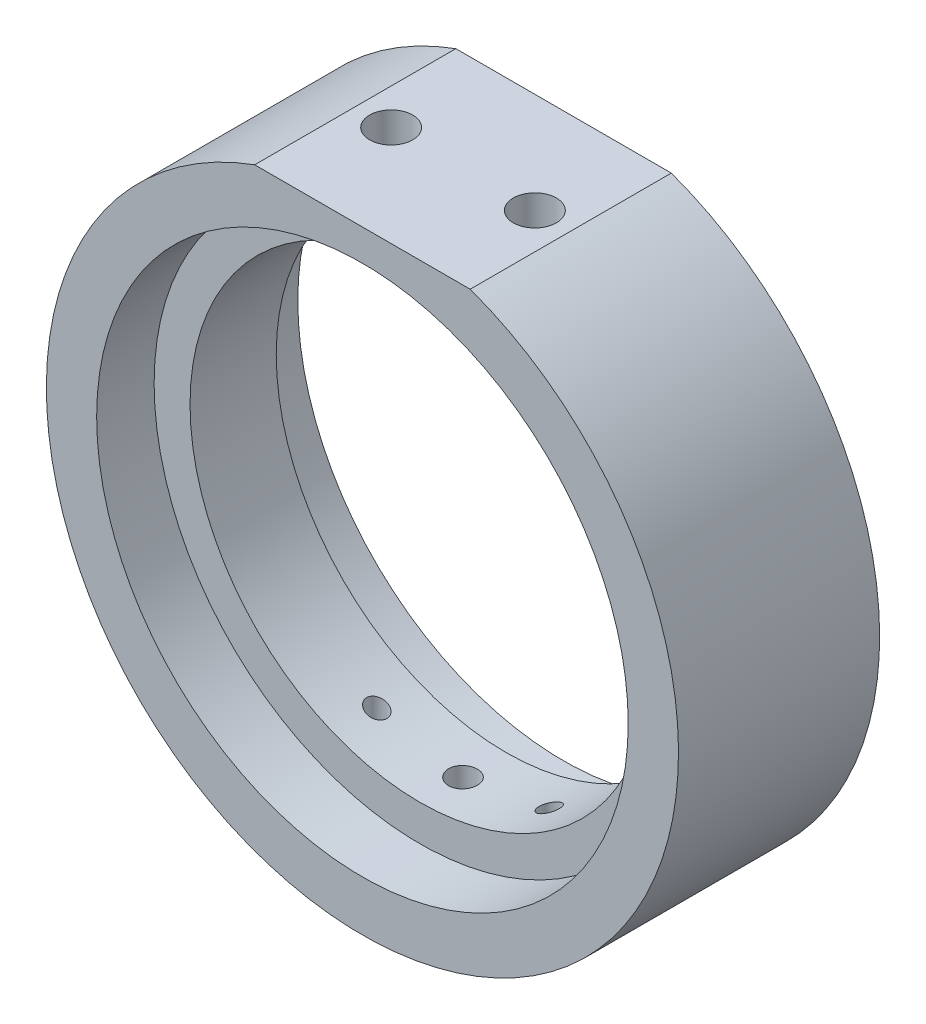
SolidWorks part; units mm, degrees
ref_plane "前视基准面" through (0, 0, 0) normal (0, 0, 1) x (1, 0, 0)
ref_plane "上视基准面" through (0, 0, 0) normal (0, 1, 0) x (1, 0, 0)
ref_plane "右视基准面" through (0, 0, 0) normal (1, 0, 0) x (0, 0, -1)
other "Configuration Table"
sketch "草图1" plane through (0, 0, 0) normal (0, 0, 1) x (1, 0, 0)
  circle A0 centre (0, 0) radius 22
  circle A1 centre (0, 0) radius 18.5
  dimension "D1" = 37
  dimension "D2" = 44
extrude "凸台-拉伸1" add sketch "草图1" along normal blind 10
sketch "草图2" plane through (0, 0, 10) normal (0, 0, 1) x (1, 0, 0)
  circle A1 centre (0, 0) radius 16
  circle A2 centre (0, 0) radius 18.5 construction
  circle A3 centre (0, 0) radius 18.5
  dimension "D1" = 32
extrude "凸台-拉伸2" add sketch "草图2" against normal blind 6
sketch "草图4" plane through (0, 0, 0) normal (0, 1, 0) x (1, 0, 0)
  line L0 (0, 0) -> (0, -10) construction
  line L1 (-22, -10) -> (22, -10) construction
  line L2 (16, -4) -> (-16, -4) construction
  line L3 (16, -4) -> (-16, -4) construction
  line L6 (-8, -8.7) -> (8, -8.7)
  line L7 (-8, -8.7) -> (-8, -6.5)
  line L8 (-8, -6.5) -> (8, -6.5)
  line L9 (8, -8.7) -> (8, -6.5)
  line L10 (-8, -8.7) -> (8, -6.5) construction
  line L11 (-8, -6.5) -> (8, -8.7) construction
  point P11 (0, -7.6)
  dimension "D1" = 2.2
  dimension "D2" = 16
  dimension "D3" = 2.5
extrude "切除-拉伸1" [suppressed] cut sketch "草图4" against normal through all
sketch "草图5" [suppressed] plane through (0, 0, 10) normal (0, 0, 1) x (1, 0, 0)
  line L0 (0, 0) -> (0, -20) construction
  line L2 (-8, -13.8564) -> (-8, -18.3303)
  line L3 (8, -18.3303) -> (8, -13.8564)
  line L4 (-8, -13.8564) -> (-8, -18.3303) construction
  line L5 (8, -18.3303) -> (8, -13.8564) construction
  circle A0 centre (0, 0) radius 18 construction
  circle A1 centre (-4, -17.5499) radius 1.5
  arc A2 (-8, -13.8564) -> (8, -13.8564) centre (0, 0) ccw
  arc A3 (-8, -18.3303) -> (8, -18.3303) centre (0, 0) ccw
  arc A4 (-8, -13.8564) -> (8, -13.8564) centre (0, 0) ccw construction
  arc A5 (-8, -18.3303) -> (8, -18.3303) centre (0, 0) ccw construction
  circle A7 centre (4, -17.5499) radius 1.5
  dimension "D2" = 36
  dimension "D3" = 3
  dimension "D4" = 4
  dimension "D1" = 0
extrude "切除-拉伸2" [suppressed] cut sketch "草图5" against normal blind 5
fillet "圆角1" [suppressed] radius 0.2
sketch "草图7" plane through (0, 0, 10) normal (0, 0, 1) x (1, 0, 0)
  line L0 (0, 0) -> (0, 22) construction
  line L1 (-7.5, 20.6821) -> (7.5, 20.6821)
  circle A0 centre (0, 0) radius 22 construction
  arc A1 (7.5, 20.6821) -> (-7.5, 20.6821) centre (0, 0) ccw
  dimension "D1" = 15
extrude "切除-拉伸3" cut sketch "草图7" against normal through all
sketch "草图8" plane through (0, 20.6821, 0) normal (0, 1, 0) x (1, 0, 0)
  line L0 (16, -4) -> (-16, -4) construction
  line L1 (16, -4) -> (-16, -4) construction
  line L2 (0, 0) -> (0, -10) construction
  line L3 (-7.5, -10) -> (7.5, -10) construction
  circle A1 centre (-5, -7) radius 1.5
  circle A2 centre (5, -7) radius 1.5
  dimension "D1" = 5
  dimension "D3" = 3
  dimension "D4" = 3
extrude "切除-拉伸4" cut sketch "草图8" against normal up to next
sketch "草图10" plane through (0, 0, 0) normal (0, 1, 0) x (1, 0, 0)
  line L0 (-16, -10) -> (16, -10) construction
  line L1 (16, -4) -> (-16, -4) construction
  line L2 (-16, -10) -> (16, -10) construction
  line L3 (16, -4) -> (-16, -4) construction
  line L4 (0, -4) -> (0, -10) construction
  circle A0 centre (0, -7) radius 1
  circle A2 centre (-6, -7) radius 1 construction
  circle A3 centre (6, -7) radius 1 construction
  circle A4 centre (-6, -7) radius 0.7
  circle A5 centre (6, -7) radius 0.7
  dimension "D1" = 2
  dimension "D3" = 12
  dimension "D4" = 0.3
  dimension "D2" = 2
extrude "切除-拉伸5" cut sketch "草图10" against normal through all
sketch "草图11" plane through (0, 0, 10) normal (0, 0, 1) x (1, 0, 0)
  line L0 (-7.5, 20.6821) -> (7.5, 20.6821) construction
  line L1 (-7.5, 20.6821) -> (7.5, 20.6821)
  circle A0 centre (0, 0) radius 18.5 construction
  circle A2 centre (0, 0) radius 18.5
  circle A4 centre (0, 0) radius 22 construction
  arc A5 (-7.5, 20.6821) -> (7.5, 20.6821) centre (0, 0) ccw
extrude "凸台-拉伸3" add sketch "草图11" along normal blind 4
